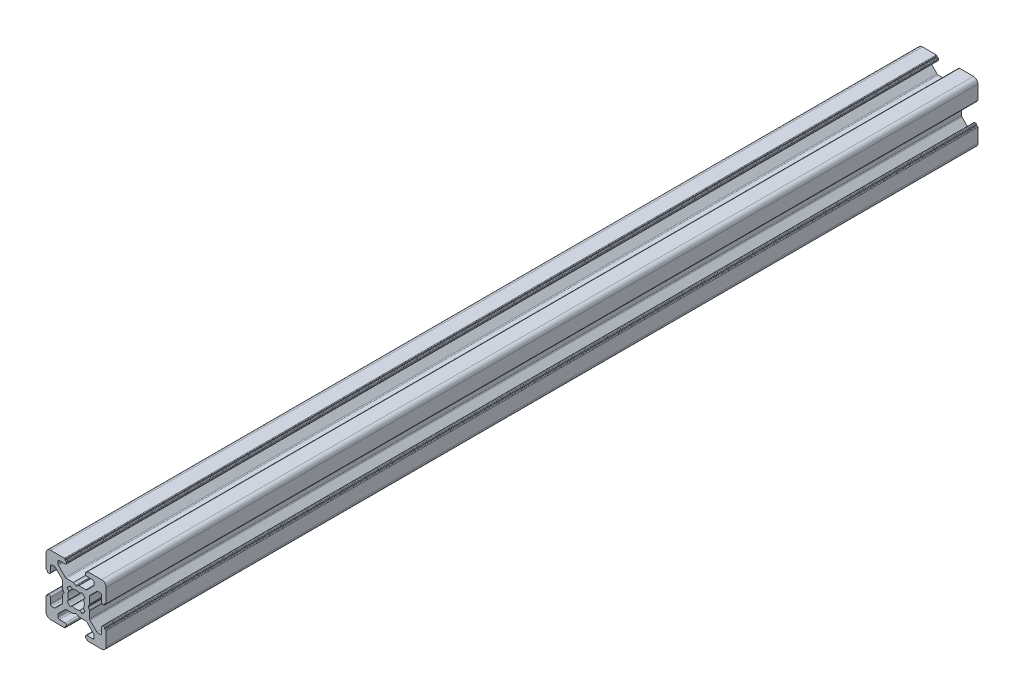
SolidWorks part; units mm, degrees
ref_plane "Ebene vorne" through (0, 0, 0) normal (0, 0, 1) x (1, 0, 0)
ref_plane "Ebene oben" through (0, 0, 0) normal (0, 1, 0) x (1, 0, 0)
ref_plane "Ebene rechts" through (0, 0, 0) normal (1, 0, 0) x (0, 0, -1)
ref_plane "Ebene1" through (0, 0, 1000) normal (0, 0, 1) x (1, 0, 0)
sketch "Skizze1" plane through (0, 0, 1000) normal (0, 0, 1) x (1, 0, 0)
  line L0 (6.0547, 11.2582) -> (5.5078, 11.9099)
  line L1 (6.5861, 12.9896) -> (7.2418, 12.4453)
  line L2 (9.7582, 12.4453) -> (10.4139, 12.9896)
  line L3 (11.4922, 11.9099) -> (10.9453, 11.2582)
  line L4 (10.9453, 8.7418) -> (11.4922, 8.0901)
  line L5 (10.4139, 7.0104) -> (9.7582, 7.5547)
  line L6 (7.2418, 7.5547) -> (6.5861, 7.0104)
  line L7 (5.5078, 8.0901) -> (6.0547, 8.7418)
  line L8 (4.85, 19.5) -> (4.85, 19.8)
  line L9 (4.65, 20) -> (0, 20)
  line L10 (-1.5, 18.5) -> (-1.5, 13.85)
  line L11 (-1.3, 13.65) -> (-1, 13.65)
  line L12 (-1, 13.65) -> (-1, 13.3)
  line L13 (-0.8, 13.1) -> (-0.5, 13.1)
  line L14 (0, 13.6) -> (0, 15.5)
  line L15 (0.5, 16) -> (1.2322, 16)
  line L16 (1.5858, 15.8536) -> (3.8536, 13.5858)
  line L17 (4, 13.2322) -> (4, 10.9536)
  line L18 (4.0268, 10.8536) -> (4.4619, 10.1)
  line L19 (4.4619, 9.9) -> (4.0268, 9.1464)
  line L20 (4, 9.0464) -> (4, 6.7678)
  line L21 (3.8536, 6.4142) -> (1.5858, 4.1464)
  line L22 (1.2322, 4) -> (0.5, 4)
  line L23 (0, 4.5) -> (0, 6.4)
  line L24 (-0.5, 6.9) -> (-0.8, 6.9)
  line L25 (-1, 6.7) -> (-1, 6.35)
  line L26 (-1, 6.35) -> (-1.3, 6.35)
  line L27 (-1.5, 6.15) -> (-1.5, 1.5)
  line L28 (0, 0) -> (4.65, 0)
  line L29 (4.85, 0.2) -> (4.85, 0.5)
  line L30 (4.85, 0.5) -> (5.2, 0.5)
  line L31 (5.4, 0.7) -> (5.4, 1)
  line L32 (4.9, 1.5) -> (3, 1.5)
  line L33 (2.5, 2) -> (2.5, 2.7322)
  line L34 (2.6464, 3.0858) -> (4.9142, 5.3536)
  line L35 (5.2678, 5.5) -> (7.5464, 5.5)
  line L36 (7.6464, 5.5268) -> (8.4, 5.9619)
  line L37 (8.6, 5.9619) -> (9.3536, 5.5268)
  line L38 (9.4536, 5.5) -> (11.7322, 5.5)
  line L39 (12.0858, 5.3536) -> (14.3536, 3.0858)
  line L40 (14.5, 2.7322) -> (14.5, 2)
  line L41 (14, 1.5) -> (12.1, 1.5)
  line L42 (11.6, 1) -> (11.6, 0.7)
  line L43 (11.8, 0.5) -> (12.15, 0.5)
  line L44 (12.15, 0.5) -> (12.15, 0.2)
  line L45 (12.35, 0) -> (17, 0)
  line L46 (18.5, 1.5) -> (18.5, 6.15)
  line L47 (18.3, 6.35) -> (18, 6.35)
  line L48 (18, 6.35) -> (18, 6.7)
  line L49 (17.8, 6.9) -> (17.5, 6.9)
  line L50 (17, 6.4) -> (17, 4.5)
  line L51 (16.5, 4) -> (15.7678, 4)
  line L52 (15.4142, 4.1464) -> (13.1464, 6.4142)
  line L53 (13, 6.7678) -> (13, 9.0464)
  line L54 (12.9732, 9.1464) -> (12.5381, 9.9)
  line L55 (12.5381, 10.1) -> (12.9732, 10.8536)
  line L56 (13, 10.9536) -> (13, 13.2322)
  line L57 (13.1464, 13.5858) -> (15.4142, 15.8536)
  line L58 (15.7678, 16) -> (16.5, 16)
  line L59 (17, 15.5) -> (17, 13.6)
  line L60 (17.5, 13.1) -> (17.8, 13.1)
  line L61 (18, 13.3) -> (18, 13.65)
  line L62 (18, 13.65) -> (18.3, 13.65)
  line L63 (18.5, 13.85) -> (18.5, 18.5)
  line L64 (17, 20) -> (12.35, 20)
  line L65 (12.15, 19.8) -> (12.15, 19.5)
  line L66 (12.15, 19.5) -> (11.8, 19.5)
  line L67 (11.6, 19.3) -> (11.6, 19)
  line L68 (12.1, 18.5) -> (14, 18.5)
  line L69 (14.5, 18) -> (14.5, 17.2678)
  line L70 (14.3536, 16.9142) -> (12.0858, 14.6464)
  line L71 (11.7322, 14.5) -> (9.4536, 14.5)
  line L72 (9.3536, 14.4732) -> (8.6, 14.0381)
  line L73 (8.4, 14.0381) -> (7.6464, 14.4732)
  line L74 (7.5464, 14.5) -> (5.2678, 14.5)
  line L75 (4.9142, 14.6464) -> (2.6464, 16.9142)
  line L76 (2.5, 17.2678) -> (2.5, 18)
  line L77 (3, 18.5) -> (4.9, 18.5)
  line L78 (5.4, 19) -> (5.4, 19.3)
  line L79 (5.2, 19.5) -> (4.85, 19.5)
  arc A0 (6.0547, 8.7418) -> (6.0547, 11.2582) centre (8.5, 10) cw
  arc A1 (5.5078, 11.9099) -> (6.5861, 12.9896) centre (8.5, 10) cw
  arc A2 (7.2418, 12.4453) -> (9.7582, 12.4453) centre (8.5, 10) cw
  arc A3 (10.4139, 12.9896) -> (11.4922, 11.9099) centre (8.5, 10) cw
  arc A4 (10.9453, 11.2582) -> (10.9453, 8.7418) centre (8.5, 10) cw
  arc A5 (11.4922, 8.0901) -> (10.4139, 7.0104) centre (8.5, 10) cw
  arc A6 (9.7582, 7.5547) -> (7.2418, 7.5547) centre (8.5, 10) cw
  arc A7 (6.5861, 7.0104) -> (5.5078, 8.0901) centre (8.5, 10) cw
  arc A8 (4.85, 19.8) -> (4.65, 20) centre (4.65, 19.8) ccw
  arc A9 (0, 20) -> (-1.5, 18.5) centre (0, 18.5) ccw
  arc A10 (-1.5, 13.85) -> (-1.3, 13.65) centre (-1.3, 13.85) ccw
  arc A11 (-1, 13.3) -> (-0.8, 13.1) centre (-0.8, 13.3) ccw
  arc A12 (-0.5, 13.1) -> (0, 13.6) centre (-0.5, 13.6) ccw
  arc A13 (0, 15.5) -> (0.5, 16) centre (0.5, 15.5) cw
  arc A14 (1.2322, 16) -> (1.5858, 15.8536) centre (1.2322, 15.5) cw
  arc A15 (3.8536, 13.5858) -> (4, 13.2322) centre (3.5, 13.2322) cw
  arc A16 (4, 10.9536) -> (4.0268, 10.8536) centre (4.2, 10.9536) ccw
  arc A17 (4.4619, 10.1) -> (4.4619, 9.9) centre (4.2887, 10) cw
  arc A18 (4.0268, 9.1464) -> (4, 9.0464) centre (4.2, 9.0464) ccw
  arc A19 (4, 6.7678) -> (3.8536, 6.4142) centre (3.5, 6.7678) cw
  arc A20 (1.5858, 4.1464) -> (1.2322, 4) centre (1.2322, 4.5) cw
  arc A21 (0.5, 4) -> (0, 4.5) centre (0.5, 4.5) cw
  arc A22 (0, 6.4) -> (-0.5, 6.9) centre (-0.5, 6.4) ccw
  arc A23 (-0.8, 6.9) -> (-1, 6.7) centre (-0.8, 6.7) ccw
  arc A24 (-1.3, 6.35) -> (-1.5, 6.15) centre (-1.3, 6.15) ccw
  arc A25 (-1.5, 1.5) -> (0, 0) centre (0, 1.5) ccw
  arc A26 (4.65, 0) -> (4.85, 0.2) centre (4.65, 0.2) ccw
  arc A27 (5.2, 0.5) -> (5.4, 0.7) centre (5.2, 0.7) ccw
  arc A28 (5.4, 1) -> (4.9, 1.5) centre (4.9, 1) ccw
  arc A29 (3, 1.5) -> (2.5, 2) centre (3, 2) cw
  arc A30 (2.5, 2.7322) -> (2.6464, 3.0858) centre (3, 2.7322) cw
  arc A31 (4.9142, 5.3536) -> (5.2678, 5.5) centre (5.2678, 5) cw
  arc A32 (7.5464, 5.5) -> (7.6464, 5.5268) centre (7.5464, 5.7) ccw
  arc A33 (8.4, 5.9619) -> (8.6, 5.9619) centre (8.5, 5.7887) cw
  arc A34 (9.3536, 5.5268) -> (9.4536, 5.5) centre (9.4536, 5.7) ccw
  arc A35 (11.7322, 5.5) -> (12.0858, 5.3536) centre (11.7322, 5) cw
  arc A36 (14.3536, 3.0858) -> (14.5, 2.7322) centre (14, 2.7322) cw
  arc A37 (14.5, 2) -> (14, 1.5) centre (14, 2) cw
  arc A38 (12.1, 1.5) -> (11.6, 1) centre (12.1, 1) ccw
  arc A39 (11.6, 0.7) -> (11.8, 0.5) centre (11.8, 0.7) ccw
  arc A40 (12.15, 0.2) -> (12.35, 0) centre (12.35, 0.2) ccw
  arc A41 (17, 0) -> (18.5, 1.5) centre (17, 1.5) ccw
  arc A42 (18.5, 6.15) -> (18.3, 6.35) centre (18.3, 6.15) ccw
  arc A43 (18, 6.7) -> (17.8, 6.9) centre (17.8, 6.7) ccw
  arc A44 (17.5, 6.9) -> (17, 6.4) centre (17.5, 6.4) ccw
  arc A45 (17, 4.5) -> (16.5, 4) centre (16.5, 4.5) cw
  arc A46 (15.7678, 4) -> (15.4142, 4.1464) centre (15.7678, 4.5) cw
  arc A47 (13.1464, 6.4142) -> (13, 6.7678) centre (13.5, 6.7678) cw
  arc A48 (13, 9.0464) -> (12.9732, 9.1464) centre (12.8, 9.0464) ccw
  arc A49 (12.5381, 9.9) -> (12.5381, 10.1) centre (12.7113, 10) cw
  arc A50 (12.9732, 10.8536) -> (13, 10.9536) centre (12.8, 10.9536) ccw
  arc A51 (13, 13.2322) -> (13.1464, 13.5858) centre (13.5, 13.2322) cw
  arc A52 (15.4142, 15.8536) -> (15.7678, 16) centre (15.7678, 15.5) cw
  arc A53 (16.5, 16) -> (17, 15.5) centre (16.5, 15.5) cw
  arc A54 (17, 13.6) -> (17.5, 13.1) centre (17.5, 13.6) ccw
  arc A55 (17.8, 13.1) -> (18, 13.3) centre (17.8, 13.3) ccw
  arc A56 (18.3, 13.65) -> (18.5, 13.85) centre (18.3, 13.85) ccw
  arc A57 (18.5, 18.5) -> (17, 20) centre (17, 18.5) ccw
  arc A58 (12.35, 20) -> (12.15, 19.8) centre (12.35, 19.8) ccw
  arc A59 (11.8, 19.5) -> (11.6, 19.3) centre (11.8, 19.3) ccw
  arc A60 (11.6, 19) -> (12.1, 18.5) centre (12.1, 19) ccw
  arc A61 (14, 18.5) -> (14.5, 18) centre (14, 18) cw
  arc A62 (14.5, 17.2678) -> (14.3536, 16.9142) centre (14, 17.2678) cw
  arc A63 (12.0858, 14.6464) -> (11.7322, 14.5) centre (11.7322, 15) cw
  arc A64 (9.4536, 14.5) -> (9.3536, 14.4732) centre (9.4536, 14.3) ccw
  arc A65 (8.6, 14.0381) -> (8.4, 14.0381) centre (8.5, 14.2113) cw
  arc A66 (7.6464, 14.4732) -> (7.5464, 14.5) centre (7.5464, 14.3) ccw
  arc A67 (5.2678, 14.5) -> (4.9142, 14.6464) centre (5.2678, 15) cw
  arc A68 (2.6464, 16.9142) -> (2.5, 17.2678) centre (3, 17.2678) cw
  arc A69 (2.5, 18) -> (3, 18.5) centre (3, 18) cw
  arc A70 (4.9, 18.5) -> (5.4, 19) centre (4.9, 19) ccw
  arc A71 (5.4, 19.3) -> (5.2, 19.5) centre (5.2, 19.3) ccw
extrude "Aufsatz-Linear austragen1" add sketch "Skizze1" against normal blind 290
